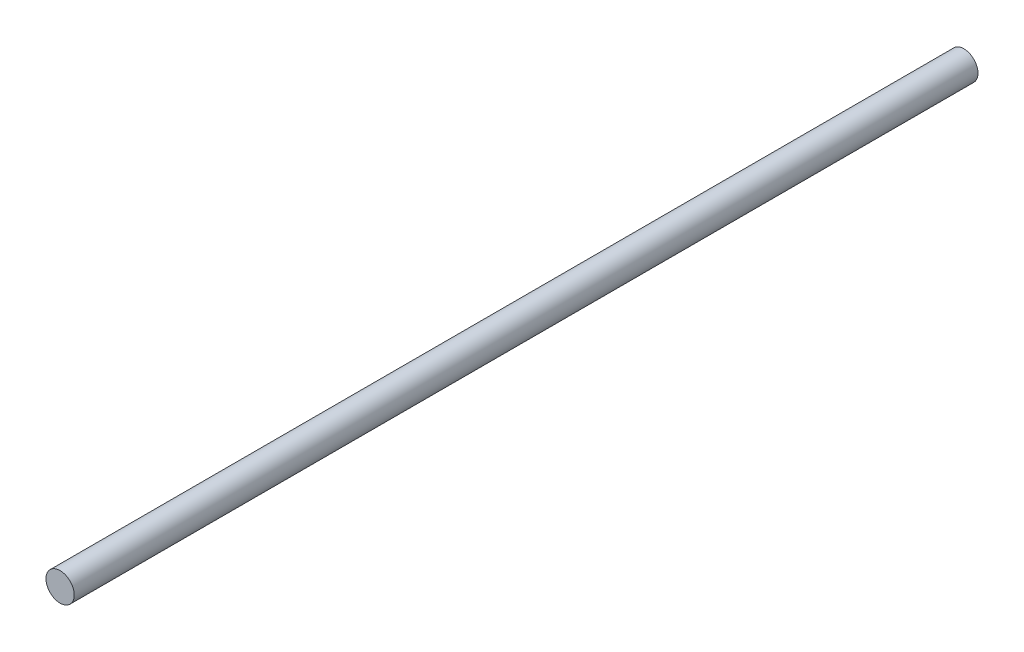
SolidWorks part; units mm, degrees
material "AISI 304"
ref_plane "Front" through (0, 0, 0) normal (0, 0, 1) x (1, 0, 0)
ref_plane "Top" through (0, 0, 0) normal (0, 1, 0) x (1, 0, 0)
ref_plane "Right" through (0, 0, 0) normal (1, 0, 0) x (0, 0, -1)
sketch "Sketch1" plane through (0, 0, 0) normal (0, 0, 1) x (1, 0, 0)
  circle A0 centre (0, 0) radius 3.175
  dimension "D1" = 6.35
extrude "Boss-Extrude1" add sketch "Sketch1" along normal mid plane 203.2
